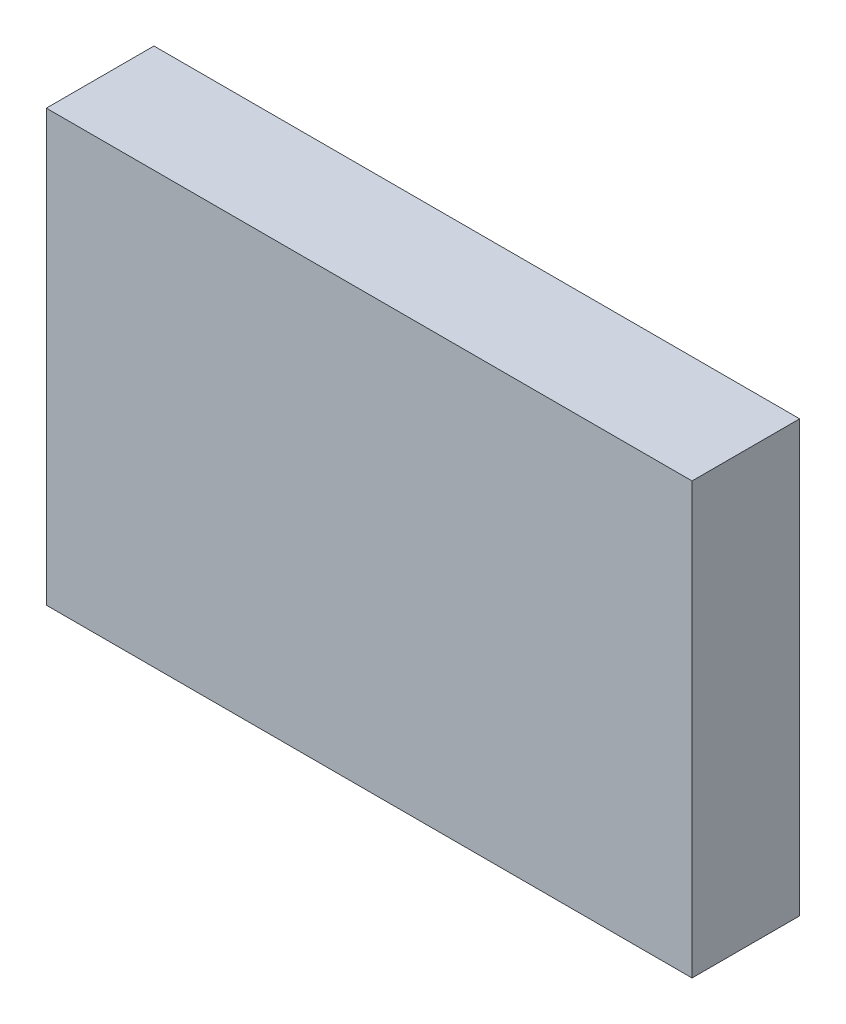
SolidWorks part; units mm, degrees
ref_plane "Front Plane" through (0, 0, 0) normal (0, 0, 1) x (1, 0, 0)
ref_plane "Top Plane" through (0, 0, 0) normal (0, 1, 0) x (1, 0, 0)
ref_plane "Right Plane" through (0, 0, 0) normal (1, 0, 0) x (0, 0, -1)
sketch "Sketch1" plane through (0, 0, 0) normal (0, 0, 1) x (1, 0, 0)
  line L1 (-15, 10) -> (15, 10)
  line L2 (-15, 10) -> (-15, -10)
  line L3 (-15, -10) -> (15, -10)
  line L4 (15, 10) -> (15, -10)
  line L5 (-15, 10) -> (15, -10) construction
  line L6 (-15, -10) -> (15, 10) construction
  point P0 (0, 0)
  dimension "D1" = 20
  dimension "D2" = 30
extrude "Boss-Extrude1" add sketch "Sketch1" along normal blind 5
